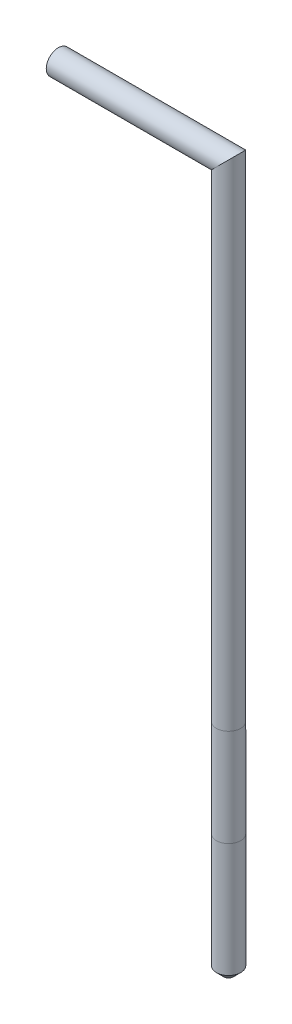
SolidWorks part; units mm, degrees
material "AISI 1020"
ref_plane "Спереди" through (0, 0, 0) normal (0, 0, 1) x (1, 0, 0)
ref_plane "Сверху" through (0, 0, 0) normal (0, 1, 0) x (1, 0, 0)
ref_plane "Справа" through (0, 0, 0) normal (1, 0, 0) x (0, 0, -1)
sketch "Эскиз1" plane through (0, 0, 0) normal (0, 0, 1) x (1, 0, 0)
  line L0 (0, 0) -> (0, 40)
  line L1 (10, 40) -> (-10, 40) construction
  line L2 (0, 40) -> (0, 240)
  line L3 (0, 240) -> (-70, 240)
  line L4 (0, 0) -> (0, -50)
  line L5 (-482.5, 0) -> (512.5, 0) construction
  line L6 (6, 230) -> (-6, 230) construction
  dimension "D1" = 50
  dimension "D2" = 10
  dimension "D3" = 70
ref_plane "Плоскость1" through (0, -50, 0) normal (0, 1, 0) x (1, 0, 0)
sketch "Эскиз2" plane through (0, -50, 0) normal (0, 1, 0) x (1, 0, 0)
  circle A0 centre (0, 0) radius 5
  dimension "D1" = 10
sweep "По траектории1" add profiles "Эскиз2" path "Эскиз1"
chamfer "Фаска1" distance 3 angle 45 1 edges at (0, -50, 5)
